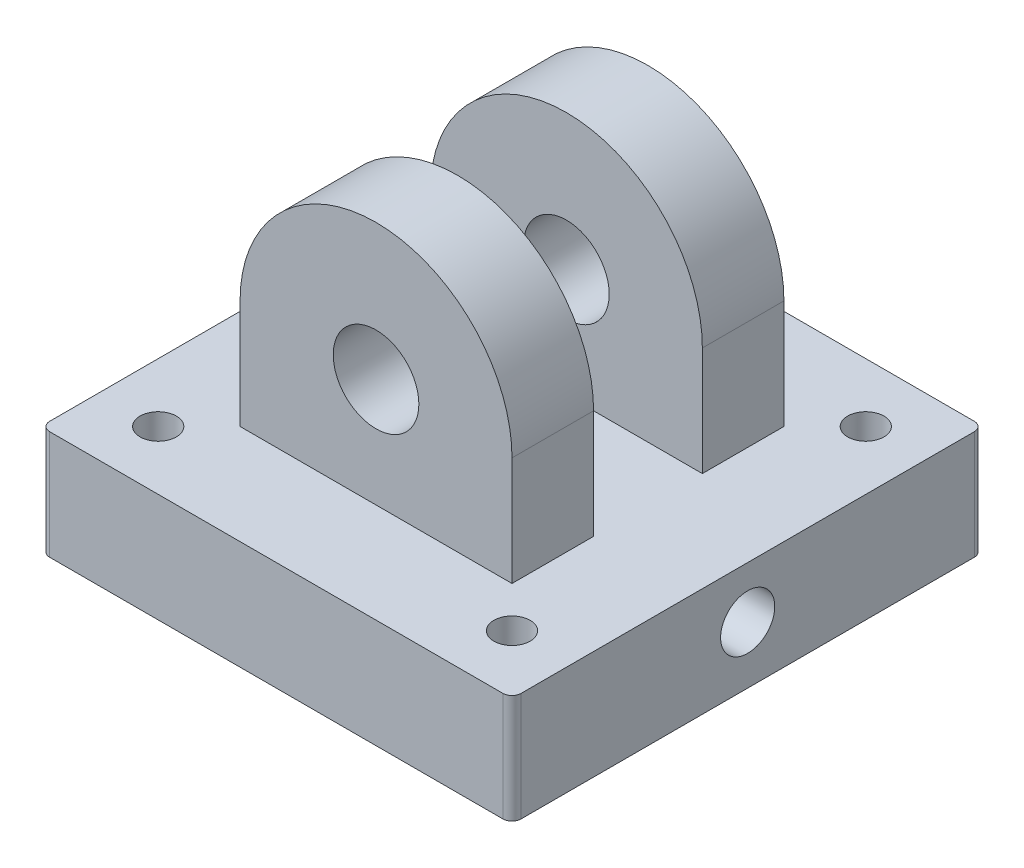
SolidWorks part; units mm, degrees
ref_plane "Front Plane" through (0, 0, 0) normal (0, 0, 1) x (1, 0, 0)
ref_plane "Top Plane" through (0, 0, 0) normal (0, 1, 0) x (1, 0, 0)
ref_plane "Right Plane" through (0, 0, 0) normal (1, 0, 0) x (0, 0, -1)
sketch "Sketch1" plane through (0, 0, 0) normal (0, 1, 0) x (1, 0, 0)
  line L1 (-79.375, -82.55) -> (79.375, -82.55)
  line L2 (-82.55, -79.375) -> (-82.55, 79.375)
  line L3 (-79.375, 82.55) -> (79.375, 82.55)
  line L4 (82.55, -79.375) -> (82.55, 79.375)
  line L5 (-82.55, -82.55) -> (82.55, 82.55) construction
  line L6 (-82.55, 82.55) -> (82.55, -82.55) construction
  arc A0 (-79.375, -82.55) -> (-82.55, -79.375) centre (-79.375, -79.375) cw
  arc A1 (79.375, -82.55) -> (82.55, -79.375) centre (79.375, -79.375) ccw
  arc A2 (79.375, 82.55) -> (82.55, 79.375) centre (79.375, 79.375) cw
  arc A3 (-82.55, 79.375) -> (-79.375, 82.55) centre (-79.375, 79.375) cw
  circle A4 centre (0, 0) radius 87.63 construction
  circle A5 centre (61.9638, 61.9638) radius 6.35
  circle A6 centre (61.9638, -61.9638) radius 6.35
  circle A7 centre (-61.9638, -61.9638) radius 6.35
  circle A8 centre (-61.9638, 61.9638) radius 6.35
  point P0 (0, 0)
  point P31 (0, 0)
  dimension "D3" = 3.175
  dimension "D4" = 175.26
  dimension "D5" = 12.7
  dimension "D1" = 165.1
  dimension "D2" = 165.1
  dimension "D6" = 4
extrude "Boss-Extrude1" add sketch "Sketch1" along normal blind 38.1
sketch "Sketch2" plane through (0, 0, 82.55) normal (0, 0, 1) x (1, 0, 0)
  line L0 (-47.625, 38.1) -> (-47.625, 76.2)
  line L1 (-79.375, 38.1) -> (79.375, 38.1) construction
  line L2 (47.625, 76.2) -> (47.625, 38.1)
  line L3 (47.625, 38.1) -> (-47.625, 38.1)
  arc A0 (-47.625, 76.2) -> (47.625, 76.2) centre (0, 76.2) cw
  circle A1 centre (0, 76.2) radius 15
  dimension "D1" = 30
  dimension "D2" = 47.625
  dimension "D3" = 38.1
extrude "Boss-Extrude2" add sketch "Sketch2" against normal blind 28.575 from offset 34.925 offset against normal yes
mirror "Mirror1" about plane through (0, 0, 0) normal (0, 0, 1) of "Boss-Extrude2"
sketch "Sketch3" plane through (0, 0, 0) normal (0, -1, 0) x (1, 0, 0)
  circle A0 centre (0, 0) radius 26
  dimension "D1" = 52
extrude "Cut-Extrude1" cut sketch "Sketch3" against normal blind 36.83
sketch "Sketch4" plane through (0, 0, 0) normal (0, -1, 0) x (1, 0, 0)
  circle A0 centre (0, 0) radius 69.85
  circle A1 centre (0, 0) radius 76.2
  dimension "D1" = 139.7
  dimension "D2" = 152.4
extrude "Cut-Extrude2" cut sketch "Sketch4" against normal blind 8
sketch "Sketch8" plane through (82.55, 0, 0) normal (1, 0, 0) x (0, 0, -1)
  line L0 (-79.375, 0) -> (79.375, 0) construction
  point P0 (0, 20.05)
  dimension "D1" = 20.05
hole_wizard "1/2-14 NPSM Tapped Hole1" positions "Sketch8" profile "Sketch9" tap size "1/2-14 NPSM" standard "ANSI Inch"
sketch "Sketch9" plane through (82.55, 20.05, 0) normal (0, 1, 0) x (0, 0, -1)
  line L0 (0, 0) -> (0, 56.55)
  line L1 (0, 56.55) -> (9.4869, 56.55)
  line L2 (9.4869, 56.55) -> (9.4869, 0)
  line L5 (9.4869, 0) -> (0, 0)
  line L11 (0, -6.35) -> (0, 107.95) construction
  dimension "Thru Tap Drill Dia." = 18.9738
  dimension "Thru Tap Drill Depth" = 56.55
cosmetic thread "Hole Thread1" parameters "D2"=20.9042
